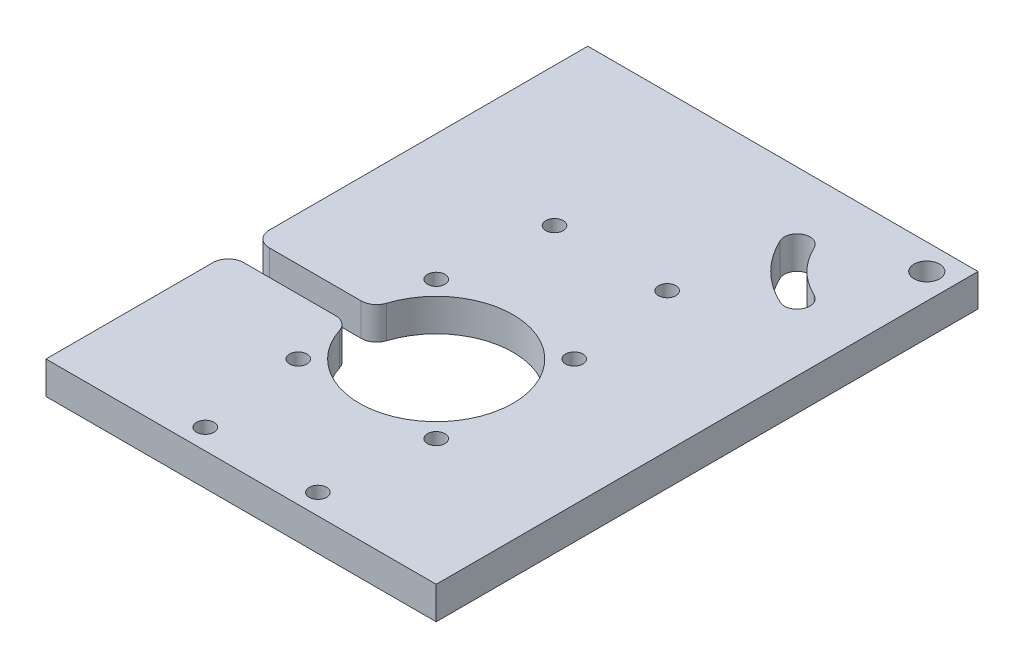
SolidWorks part; units mm, degrees
ref_plane "Front" through (0, 0, 0) normal (0, 0, 1) x (1, 0, 0)
ref_plane "Top" through (0, 0, 0) normal (0, 1, 0) x (1, 0, 0)
ref_plane "Right" through (0, 0, 0) normal (1, 0, 0) x (0, 0, -1)
sketch "Sketch1" plane through (0, 0, 0) normal (0, 1, 0) x (1, 0, 0)
  line L0 (-38.1, 0) -> (0, 0) construction
  line L1 (-38.1, 67.7) -> (38.1, 67.7)
  line L3 (-38.1, -38.1) -> (38.1, -38.1)
  line L4 (38.1, 67.7) -> (38.1, -38.1)
  line L5 (0, 0) -> (0, -38.1) construction
  line L6 (19.6296, 49.2296) -> (33.1, 62.7) construction
  line L11 (-38.1, 67.7) -> (-38.1, 2.5)
  line L12 (-38.1, 2.5) -> (-14.7902, 2.5)
  line L13 (-14.7902, -2.5) -> (-38.1, -2.5)
  line L14 (-38.1, -2.5) -> (-38.1, -38.1)
  circle A1 centre (0, 0) radius 28.575 construction
  circle A2 centre (33.1, 62.7) radius 2.5
  arc A3 (26.1057, 47.7006) -> (18.1006, 55.7057) centre (33.1, 62.7) cw
  arc A4 (23.9926, 43.1691) -> (13.5691, 53.5926) centre (33.1, 62.7) cw
  arc A5 (18.1006, 55.7057) -> (13.5691, 53.5926) centre (15.8348, 54.6491) ccw
  arc A6 (23.9926, 43.1691) -> (26.1057, 47.7006) centre (25.0491, 45.4348) ccw
  arc A7 (15.8348, 54.6491) -> (25.0491, 45.4348) centre (33.1, 62.7) ccw construction
  arc A8 (-14.7902, 2.5) -> (-14.7902, -2.5) centre (0, 0) cw
  point P9 (0, -38.1)
  dimension "D3" = 57.15
  dimension "D6" = 5
  dimension "D9" = 45
  dimension "D12" = 15
  dimension "D2" = 76.2
  dimension "D4" = 67.7
  dimension "D5" = 19.05
  dimension "D7" = 5
  dimension "D8" = 5
  dimension "D10" = 40
  dimension "D11" = 5
extrude "Boss-Extrude1" add sketch "Sketch1" along normal blind 6.35
hole_wizard "M3 Clearance Hole1" positions "Sketch2" profile "Sketch4" hole size "M3" standard "ANSI Metric" end condition through all
sketch "Sketch2" plane through (0, 6.35, 0) normal (0, 1, 0) x (1, 0, 0)
  line L0 (0, 0) -> (13.4704, 13.4704) construction
  line L1 (-38.1, -38.1) -> (38.1, -38.1) construction
  point P0 (13.4704, 13.4704)
  dimension "D1" = 19.05
  dimension "D2" = 45
sketch "Sketch4" plane through (13.4704, 6.35, -13.4704) normal (1, 0, 0) x (0, 0, 1)
  line L0 (0, 0) -> (0, 6.35)
  line L1 (0, 6.35) -> (1.7, 6.35)
  line L2 (1.7, 6.35) -> (1.7, 0)
  line L5 (1.7, 0) -> (0, 0)
  line L11 (0, -6.35) -> (0, 107.95) construction
  dimension "Thru Hole Dia." = 3.4
  dimension "Thru Hole Depth" = 6.35
pattern_circular "CirPattern1" count 4 over 360 about axis through (0, 0, 0) along (0, 1, 0) of "M3 Clearance Hole1"
hole_wizard "M3 Clearance Hole3" positions "Sketch7" profile "Sketch8" hole size "M3" standard "ANSI Metric" end condition through all
sketch "Sketch7" plane through (0, 6.35, 0) normal (0, 1, 0) x (1, 0, 0)
  line L1 (-15, 38.1) -> (15, 38.1)
  line L2 (-15, 38.1) -> (-15, -38.1)
  line L3 (-15, -38.1) -> (15, -38.1)
  line L4 (15, 38.1) -> (15, -38.1)
  point P140 (15, 0)
  point P142 (0, 38.1)
  point P288 (-11, -34.1)
  point P290 (11, -34.1)
  point P292 (-11, 34.1)
  point P294 (11, 34.1)
  dimension "D1" = 30
  dimension "D2" = 76.2
  dimension "D3" = 4
  dimension "D4" = 4
  dimension "D5" = 4
  dimension "D6" = 4
sketch "Sketch8" plane through (11, 6.35, -34.1) normal (1, 0, 0) x (0, 0, 1)
  line L0 (0, 0) -> (0, 6.35)
  line L1 (0, 6.35) -> (1.7, 6.35)
  line L2 (1.7, 6.35) -> (1.7, 0)
  line L5 (1.7, 0) -> (0, 0)
  line L11 (0, -6.35) -> (0, 107.95) construction
  dimension "Thru Hole Dia." = 3.4
  dimension "Thru Hole Depth" = 6.35
fillet "Fillet1" radius 3 4 edges at (-38.1, 3.175, 2.5) (-38.1, 3.175, -2.5) (-14.7902, 3.175, 2.5) (-14.7902, 3.175, -2.5)
